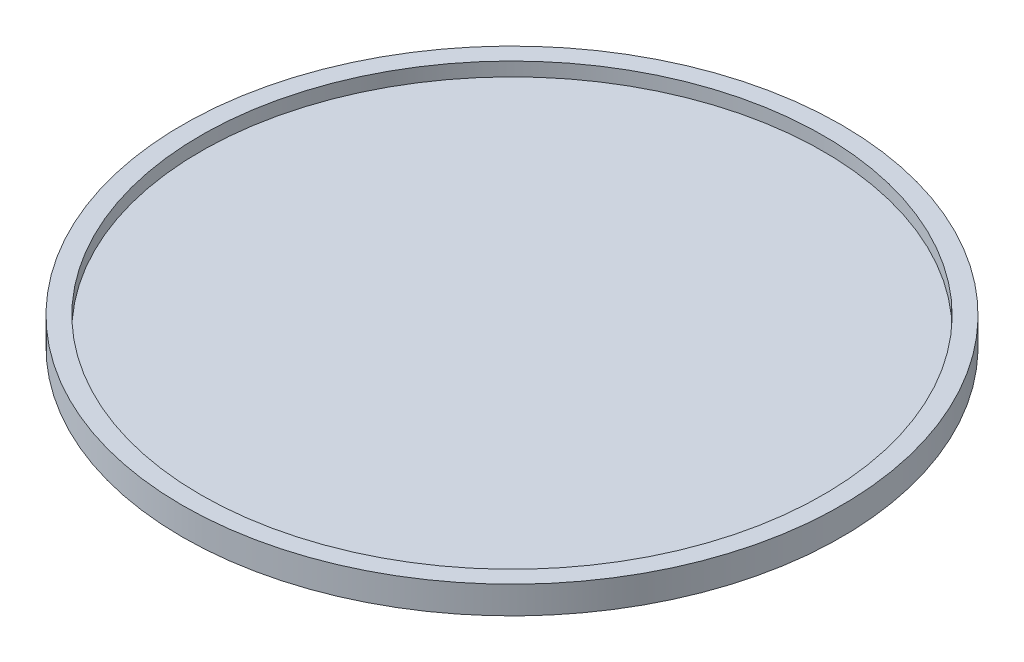
SolidWorks part; units mm, degrees
material "Thornel VCB-20 Carbon Cloth"
ref_plane "Front Plane" through (0, 0, 0) normal (0, 0, 1) x (1, 0, 0)
ref_plane "Top Plane" through (0, 0, 0) normal (0, 1, 0) x (1, 0, 0)
ref_plane "Right Plane" through (0, 0, 0) normal (1, 0, 0) x (0, 0, -1)
sketch "Sketch1" plane through (0, 0, 0) normal (0, 1, 0) x (1, 0, 0)
  circle A0 centre (0, 0) radius 18
extrude "Boss-Extrude1" add sketch "Sketch1" along normal blind 1.5
sketch "Sketch2" plane through (0, 1.5, 0) normal (0, 1, 0) x (1, 0, 0)
  circle A0 centre (0, 0) radius 17
extrude "Cut-Extrude1" cut sketch "Sketch2" against normal blind 0.75
